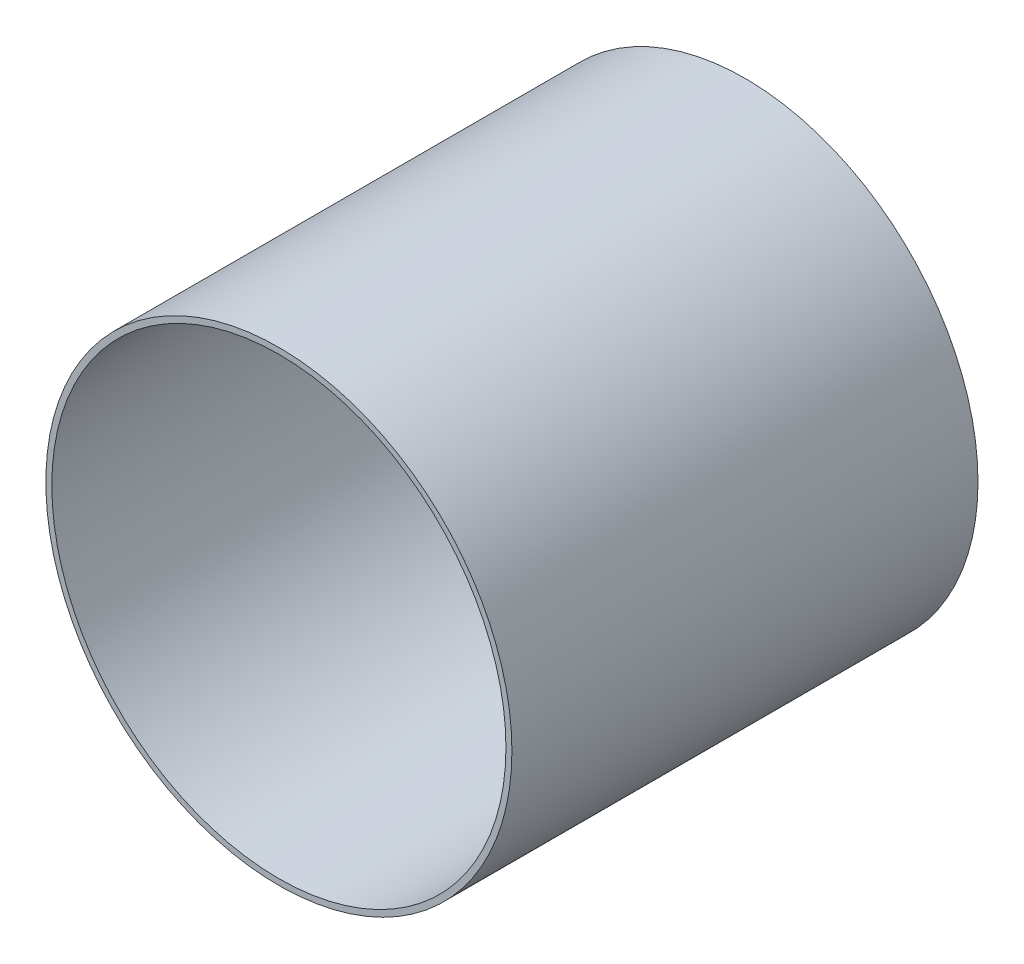
SolidWorks part; units mm, degrees
other "Markup1"
sketch "Sketch3" plane through (-156, -156, 4) normal (0, 0, 1) x (1, 0, 0)
material "E-Glass Fiber"
ref_plane "Front Plane" through (0, 0, 0) normal (0, 0, 1) x (1, 0, 0)
ref_plane "Top Plane" through (0, 0, 0) normal (0, 1, 0) x (1, 0, 0)
ref_plane "Right Plane" through (0, 0, 0) normal (1, 0, 0) x (0, 0, -1)
sketch "Sketch1" plane through (0, 0, 0) normal (0, 0, 1) x (1, 0, 0)
  circle A1 centre (0, 0) radius 156
  point P1 (0, 0)
extrude "Boss-Extrude1" add sketch "Sketch1" along normal blind 312
sketch "Sketch2" plane through (0, 0, 312) normal (0, 0, 1) x (1, 0, 0)
  circle A0 centre (0, 0) radius 152
  point P3 (0, 0)
extrude "Cut-Extrude1" cut sketch "Sketch2" against normal blind 312 contours A0
